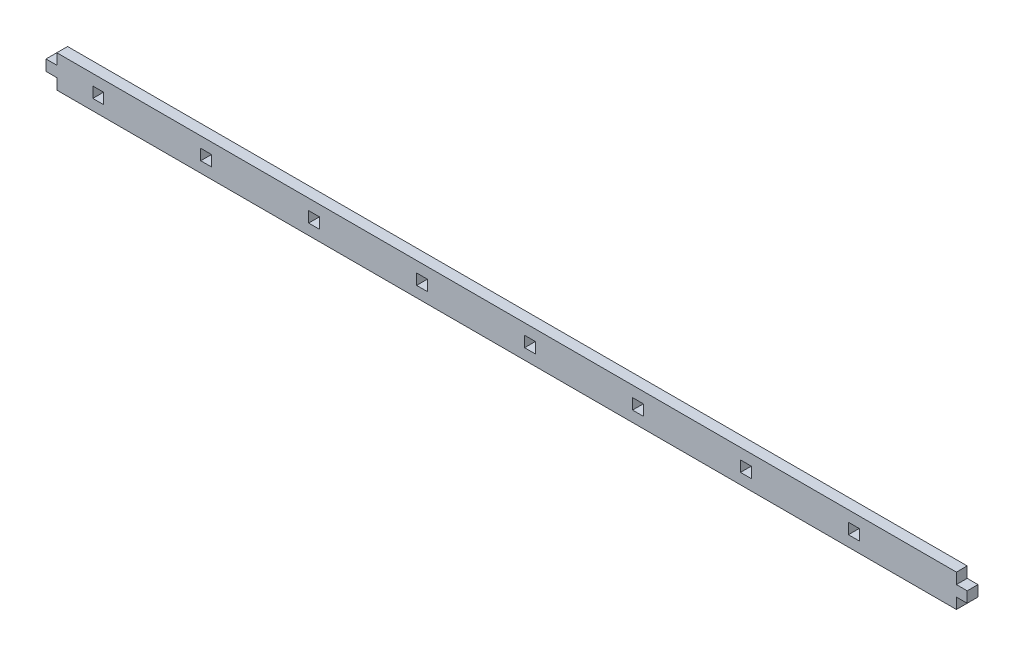
SolidWorks part; units mm, degrees
ref_plane "Front Plane" through (0, 0, 0) normal (0, 0, 1) x (1, 0, 0)
ref_plane "Top Plane" through (0, 0, 0) normal (0, 1, 0) x (1, 0, 0)
ref_plane "Right Plane" through (0, 0, 0) normal (1, 0, 0) x (0, 0, -1)
sketch "Sketch2" plane through (0, 0, 0) normal (0, 0, 1) x (1, 0, 0)
  line L0 (-3, 4.5) -> (-10.7478, 4.5) construction
  line L1 (0, 0) -> (250, 0)
  line L2 (0, 0) -> (0, 3)
  line L3 (0, 9) -> (250, 9)
  line L4 (250, 0) -> (250, 3)
  line L5 (0, 6) -> (-3, 6)
  line L7 (0, 3) -> (-3, 3)
  line L8 (-3, 6) -> (-3, 3)
  line L9 (10, 6) -> (13, 6)
  line L10 (10, 6) -> (10, 3)
  line L11 (10, 3) -> (13, 3)
  line L12 (13, 6) -> (13, 3)
  line L13 (13, 4.5) -> (10, 4.5) construction
  line L14 (40, 6) -> (40, 3)
  line L15 (40, 6) -> (43, 6)
  line L16 (43, 6) -> (43, 3)
  line L17 (40, 3) -> (43, 3)
  line L18 (70, 6) -> (70, 3)
  line L19 (70, 6) -> (73, 6)
  line L20 (73, 6) -> (73, 3)
  line L21 (70, 3) -> (73, 3)
  line L22 (100, 6) -> (100, 3)
  line L23 (100, 6) -> (103, 6)
  line L24 (103, 6) -> (103, 3)
  line L25 (100, 3) -> (103, 3)
  line L26 (130, 6) -> (130, 3)
  line L27 (130, 6) -> (133, 6)
  line L28 (133, 6) -> (133, 3)
  line L29 (130, 3) -> (133, 3)
  line L30 (160, 6) -> (160, 3)
  line L31 (160, 6) -> (163, 6)
  line L32 (163, 6) -> (163, 3)
  line L33 (160, 3) -> (163, 3)
  line L34 (190, 6) -> (190, 3)
  line L35 (190, 6) -> (193, 6)
  line L36 (193, 6) -> (193, 3)
  line L37 (190, 3) -> (193, 3)
  line L38 (125, 9) -> (125, 35.2284) construction
  line L39 (250, 3) -> (253, 3)
  line L40 (253, 6) -> (253, 3)
  line L41 (250, 6) -> (253, 6)
  line L43 (0, 6) -> (0, 9)
  line L44 (250, 6) -> (250, 9)
  line L45 (220, 6) -> (220, 3)
  line L46 (220, 6) -> (223, 6)
  line L47 (223, 6) -> (223, 3)
  line L48 (220, 3) -> (223, 3)
  dimension "D1" = 250
  dimension "D2" = 3
  dimension "D3" = 3
  dimension "D4" = 3
  dimension "D5" = 3
  dimension "D6" = 3
  dimension "D7" = 3
  dimension "D8" = 10
  dimension "D10" = 27
  dimension "D9" = 8
extrude "Boss-Extrude3" add sketch "Sketch2" along normal blind 3
